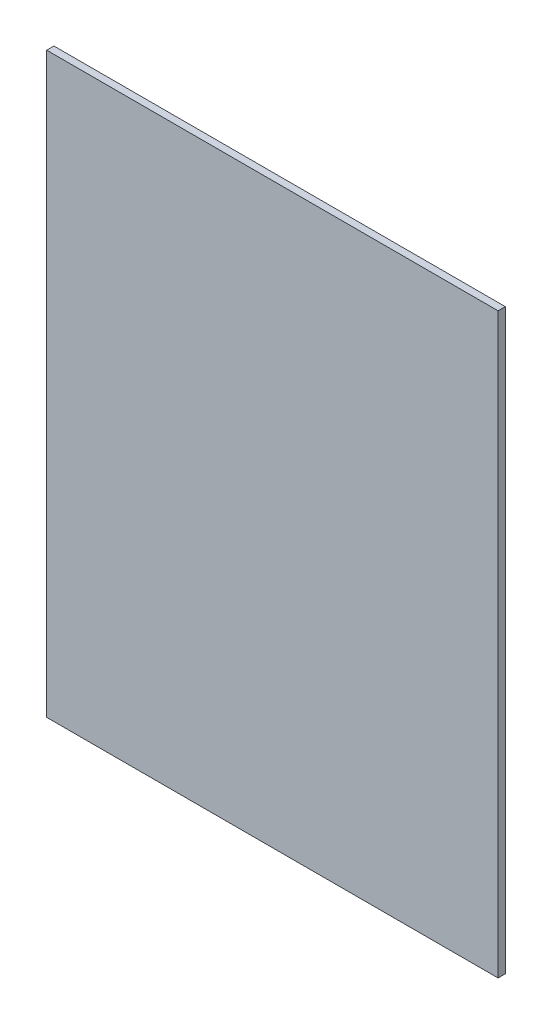
SolidWorks part; units mm, degrees
material "Glass"
ref_plane "Front Plane" through (0, 0, 0) normal (0, 0, 1) x (1, 0, 0)
ref_plane "Top Plane" through (0, 0, 0) normal (0, 1, 0) x (1, 0, 0)
ref_plane "Right Plane" through (0, 0, 0) normal (1, 0, 0) x (0, 0, -1)
ref_plane "Plane1" through (0, 0, -54.2249) normal (0, 0, 1) x (1, 0, 0)
sketch "Sketch1" plane through (0, 0, -54.2249) normal (0, 0, 1) x (1, 0, 0)
  line L0 (-145, 140) -> (-145, -180)
  line L1 (-145, -180) -> (105, -180)
  line L2 (105, -180) -> (105, 140)
  line L3 (105, 140) -> (-145, 140)
extrude "Boss-Extrude1" add sketch "Sketch1" against normal blind 4
ref_plane "Plane2" through (-20, 0, 0) normal (1, 0, 0) x (0, 0, -1)
ref_plane "Plane3" through (0, -20, 0) normal (0, -1, 0) x (-1, 0, 0)
